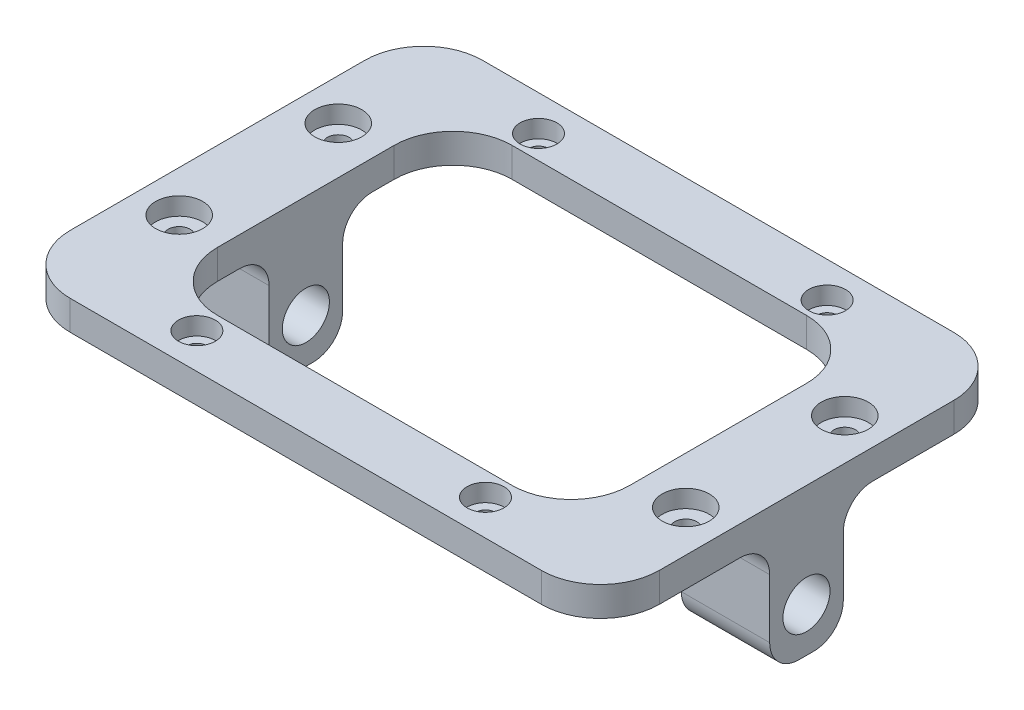
SolidWorks part; units mm, degrees
ref_plane "Front Plane" through (0, 0, 0) normal (0, 0, 1) x (1, 0, 0)
ref_plane "Top Plane" through (0, 0, 0) normal (0, 1, 0) x (1, 0, 0)
ref_plane "Right Plane" through (0, 0, 0) normal (1, 0, 0) x (0, 0, -1)
sketch "Sketch1" plane through (0, 0, 0) normal (0, 1, 0) x (1, 0, 0)
  line L1 (50, -35) -> (-50, -35)
  line L2 (50, -35) -> (50, 35)
  line L3 (50, 35) -> (-50, 35)
  line L4 (-50, -35) -> (-50, 35)
  line L5 (50, -35) -> (-50, 35) construction
  line L6 (50, 35) -> (-50, -35) construction
  point P0 (0, 0)
  dimension "D1" = 70
  dimension "D2" = 100
extrude "Boss-Extrude1" add sketch "Sketch1" along normal blind 5
fillet "Fillet1" radius 10 4 edges at (50, 2.5, 35) (50, 2.5, -35) (-50, 2.5, -35) (-50, 2.5, 35)
sketch "Sketch2" plane through (0, 5, 0) normal (0, 1, 0) x (1, 0, 0)
  circle A0 centre (-43, 13.5) radius 1.85
  dimension "D1" = 3.7
  dimension "D2" = 43
  dimension "D3" = 13.5
extrude "Cut-Extrude1" cut sketch "Sketch2" against normal up to next
mirror "Mirror1" about plane through (0, 0, 0) normal (1, 0, 0) of "Cut-Extrude1" second plane through (0, 0, 0) second plane normal (0, 0, 1)
sketch "Sketch3" plane through (0, 5, 0) normal (0, 1, 0) x (1, 0, 0)
  circle A0 centre (-24.5, 29) radius 1.625
  dimension "D1" = 3.25
  dimension "D3" = 24.5
  dimension "D2" = 29
extrude "Cut-Extrude2" cut sketch "Sketch3" against normal up to next
mirror "Mirror2" about plane through (0, 0, 0) normal (1, 0, 0) of "Cut-Extrude2" second plane through (0, 0, 0) second plane normal (0, 0, 1)
sketch "Sketch4" plane through (0, 5, 0) normal (0, 1, 0) x (1, 0, 0)
  line L0 (40, 35) -> (-40, 35) construction
  line L1 (35, -25) -> (-35, -25)
  line L2 (35, -25) -> (35, 25)
  line L3 (35, 25) -> (-35, 25)
  line L4 (-35, -25) -> (-35, 25)
  line L5 (35, -25) -> (-35, 25) construction
  line L6 (35, 25) -> (-35, -25) construction
  line L7 (-50, 25) -> (-50, -25) construction
  point P0 (0, 0)
  dimension "D1" = 10
  dimension "D2" = 15
extrude "Cut-Extrude3" cut sketch "Sketch4" against normal up to next
fillet "Fillet2" radius 10 4 edges at (35, 2.5, -25) (35, 2.5, 25) (-35, 2.5, 25) (-35, 2.5, -25)
sketch "Sketch5" plane through (0, 5, 0) normal (0, 1, 0) x (1, 0, 0)
  circle A0 centre (-24.5, 29) radius 3.125
  circle A1 centre (-24.5, 29) radius 1.625 construction
  dimension "D1" = 1.5
extrude "Cut-Extrude4" cut sketch "Sketch5" against normal blind 3
mirror "Mirror3" about plane through (0, 0, 0) normal (0, 0, 1) of "Cut-Extrude4" second plane through (0, 0, 0) second plane normal (1, 0, 0)
sketch "Sketch6" plane through (0, 5, 0) normal (0, 1, 0) x (1, 0, 0)
  circle A0 centre (-43, 13.5) radius 4
  dimension "D1" = 8
extrude "Cut-Extrude5" cut sketch "Sketch6" against normal blind 3
mirror "Mirror4" about plane through (0, 0, 0) normal (1, 0, 0) of "Cut-Extrude5" second plane through (0, 0, 0) second plane normal (0, 0, 1)
sketch "Sketch9" plane through (0, 0, 0) normal (0, -1, 0) x (1, 0, 0)
  line L0 (-50, -25) -> (-50, 25) construction
  line L1 (-35, -6.25) -> (-50, -6.25)
  line L2 (-35, -6.25) -> (-35, 6.25)
  line L3 (-35, 6.25) -> (-50, 6.25)
  line L4 (-50, -6.25) -> (-50, 6.25)
  line L5 (-35, -6.25) -> (-50, 6.25) construction
  line L6 (-35, 6.25) -> (-50, -6.25) construction
  line L7 (-35, 15) -> (-35, -15) construction
  line L8 (-50, 0) -> (50, 0) construction
  line L9 (50, 25) -> (50, -25) construction
  line L10 (35, -15) -> (35, 15) construction
  line L11 (50, -6.25) -> (35, -6.25)
  line L12 (50, -6.25) -> (50, 6.25)
  line L13 (50, 6.25) -> (35, 6.25)
  line L14 (35, -6.25) -> (35, 6.25)
  line L15 (50, -6.25) -> (35, 6.25) construction
  line L16 (50, 6.25) -> (35, -6.25) construction
  point P0 (-42.5, 0)
  point P16 (42.5, 0)
  point P21 (50, 8.9094)
  point P22 (41.6963, 0)
  point P23 (50, -6.25)
  dimension "D1" = 12.5
  dimension "D2" = 12.5
extrude "Boss-Extrude3" add sketch "Sketch9" along normal blind 20
sketch "Sketch10" plane through (-50, 0, 0) normal (-1, 0, 0) x (0, 0, 1)
  line L0 (0, 0) -> (0, -12.5) construction
  circle A0 centre (0, -12.5) radius 4
  dimension "D1" = 8
  dimension "D2" = 12.5
extrude "Cut-Extrude7" cut sketch "Sketch10" against normal up to surface (100 mm away) up to face at (50, -3.75, 0)
fillet "Fillet4" radius 5 8 edges at (42.5, 0, 6.25) (42.5, 0, -6.25) (42.5, -20, 6.25) (42.5, -20, -6.25) (-42.5, 0, -6.25) (-42.5, -20, -6.25) (-42.5, -20, 6.25) (-42.5, 0, 6.25)
